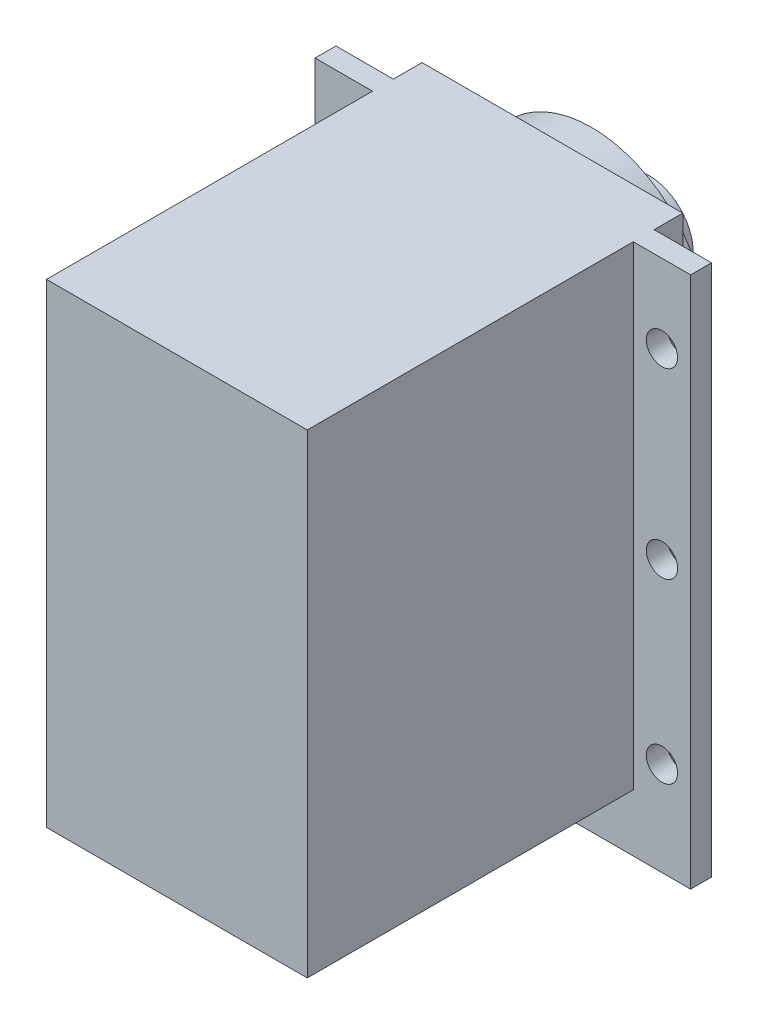
SolidWorks part; units mm, degrees
ref_plane "Front Plane" through (0, 0, 0) normal (0, 0, 1) x (1, 0, 0)
ref_plane "Top Plane" through (0, 0, 0) normal (0, 1, 0) x (1, 0, 0)
ref_plane "Right Plane" through (0, 0, 0) normal (1, 0, 0) x (0, 0, -1)
sketch "Sketch1" plane through (0, 0, 0) normal (0, 0, 1) x (1, 0, 0)
  line L1 (-12.5, -22.75) -> (12.5, -22.75)
  line L2 (-12.5, -22.75) -> (-12.5, 22.75)
  line L3 (-12.5, 22.75) -> (12.5, 22.75)
  line L4 (12.5, -22.75) -> (12.5, 22.75)
  line L5 (-12.5, -22.75) -> (12.5, 22.75) construction
  line L6 (-12.5, 22.75) -> (12.5, -22.75) construction
  point P0 (0, 0)
  dimension "D1" = 25
  dimension "D2" = 45.5
extrude "Boss-Extrude1" add sketch "Sketch1" along normal blind 36
sketch "Sketch2" plane through (0, 0, 0) normal (0, 0, -1) x (-1, 0, 0)
  line L0 (-12.5, 22.75) -> (12.5, 22.75) construction
  line L1 (-18, 22.75) -> (18, 22.75)
  line L2 (-18, 22.75) -> (-18, -28.25)
  line L3 (-18, -28.25) -> (18, -28.25)
  line L4 (18, 22.75) -> (18, -28.25)
  line L5 (-12.5, -22.75) -> (-12.5, 22.75) construction
  line L6 (12.5, 22.75) -> (12.5, -22.75) construction
  line L7 (12.5, -22.75) -> (-12.5, -22.75) construction
  line L8 (-18, 20.9329) -> (-12.5, 20.9329) construction
  line L9 (12.5, 18.8932) -> (18, 18.8932) construction
  line L10 (2.0803, -28.25) -> (2.0803, -22.75) construction
  circle A0 centre (-15.25, 15.25) radius 1.5
  circle A1 centre (-15.25, -2.25) radius 1.5
  circle A2 centre (-15.25, -19.25) radius 1.5
  circle A3 centre (-7.5, -25.5) radius 1.5
  circle A4 centre (7.5, -25.5) radius 1.5
  circle A5 centre (15.25, -19.25) radius 1.5
  circle A6 centre (15.25, -2.25) radius 1.5
  circle A7 centre (15.25, 15.25) radius 1.5
  point P28 (2.0803, -25.5)
  point P29 (-15.25, 20.9329)
  point P32 (15.25, 18.8932)
  dimension "D4" = 3
  dimension "D5" = 7.5
  dimension "D1" = 5.5
  dimension "D2" = 5.5
  dimension "D3" = 5.5
  dimension "D6" = 25
  dimension "D7" = 42
  dimension "D8" = 5
  dimension "D9" = 5
extrude "Boss-Extrude2" add sketch "Sketch2" against normal blind 2 from offset 2.75 offset against normal yes
sketch "Sketch3" plane through (0, 0, 0) normal (0, 0, -1) x (-1, 0, 0)
  line L0 (-12.5, 22.75) -> (12.5, 22.75) construction
  circle A0 centre (0, 10.75) radius 11
  point P5 (0, 22.75)
  dimension "D1" = 22
  dimension "D2" = 12
extrude "Boss-Extrude3" add sketch "Sketch3" along normal blind 3.75
sketch "Sketch4" plane through (0, 0, -3.75) normal (0, 0, -1) x (-1, 0, 0)
  circle A0 centre (0, 18.75) radius 1.5
  circle A1 centre (0, 10.75) radius 11 construction
  circle A2 centre (-5.6569, 16.4069) radius 1.5
  circle A3 centre (-8, 10.75) radius 1.5
  circle A4 centre (-5.6569, 5.0931) radius 1.5
  circle A5 centre (0, 2.75) radius 1.5
  circle A6 centre (5.6569, 5.0931) radius 1.5
  circle A7 centre (8, 10.75) radius 1.5
  circle A8 centre (5.6569, 16.4069) radius 1.5
  point P21 (0, 10.75)
  dimension "D1" = 3
  dimension "D2" = 8
  dimension "D3" = 8
extrude "Cut-Extrude1" cut sketch "Sketch4" against normal blind 3.75
sketch "Sketch5" plane through (0, 0, -3.75) normal (0, 0, -1) x (-1, 0, 0)
  circle A0 centre (0, 10.75) radius 4.25
  dimension "D1" = 8.5
extrude "Boss-Extrude4" add sketch "Sketch5" along normal blind 5.5
